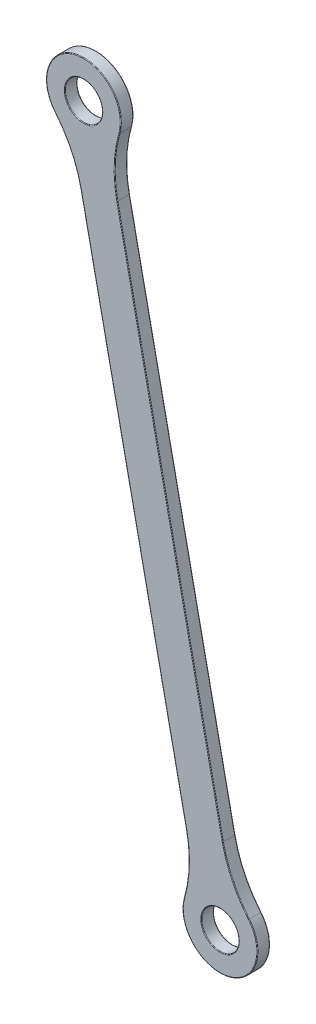
SolidWorks part; units mm, degrees
material "AISI 1020"
ref_plane "Front Plane" through (0, 0, 0) normal (0, 0, 1) x (1, 0, 0)
ref_plane "Top Plane" through (0, 0, 0) normal (0, 1, 0) x (1, 0, 0)
ref_plane "Right Plane" through (0, 0, 0) normal (1, 0, 0) x (0, 0, -1)
sketch "Sketch1" plane through (0, 0, 0) normal (0, 0, 1) x (1, 0, 0)
  line L0 (30.4151, 76.3439) -> (-2.4827, 232.9253) construction
  line L1 (30.4151, 76.3439) -> (-2.4827, 232.9253) construction
  line L2 (-2.4827, 232.9253) -> (30.4151, 76.3439) construction
  line L3 (1.9212, 233.8505) -> (34.819, 77.2691)
  line L4 (-6.8865, 232) -> (26.0113, 75.4186)
  circle A0 centre (-2.4827, 232.9253) radius 9
  circle A1 centre (30.4151, 76.3439) radius 9
  arc A2 (1.9212, 233.8505) -> (-6.8865, 232) centre (-2.4827, 232.9253) ccw
  arc A3 (26.0113, 75.4186) -> (34.819, 77.2691) centre (30.4151, 76.3439) ccw
  arc A4 (1.9212, 233.8505) -> (-6.8865, 232) centre (-2.4827, 232.9253) cw
  arc A5 (26.0113, 75.4186) -> (34.819, 77.2691) centre (30.4151, 76.3439) cw
  point P5 (13.9662, 154.6346)
  dimension "D1" = 18
  dimension "D2" = 9
extrude "Boss-Extrude1" add sketch "Sketch1" along normal blind 3 contours A2 L3 A0 L4 | L3 A4 L4 A0 | A1 L3 A0 L4 | A3 L4 A1 L3 | L4 A5 L3 A1
fillet "Fillet1" radius 30 4 edges at (3.5237, 226.2228, 1.5) (-5.284, 224.3723, 1.5) (24.4087, 83.0463, 1.5) (33.2164, 84.8968, 1.5)
fillet "Fillet2" radius 0.15 20 edges at (2.0173, 232.9253, 3) (2.0173, 232.9253, 0) (33.4207, 88.1958, 3) (33.4207, 88.1958, 0) (32.2656, 67.5362, 3) (32.2656, 67.5362, 0) (22.894, 85.9842, 3) (22.894, 85.9842, 0) (9.5624, 153.7093, 3) (9.5624, 153.7093, 0) (-5.4883, 221.0733, 3) (-5.4883, 221.0733, 0) (-4.3332, 241.733, 3) (-4.3332, 241.733, 0) (5.0384, 223.2849, 3) (5.0384, 223.2849, 0) (18.3701, 155.5598, 0) (18.3701, 155.5598, 3) (34.9151, 76.3439, 3) (34.9151, 76.3439, 0)
